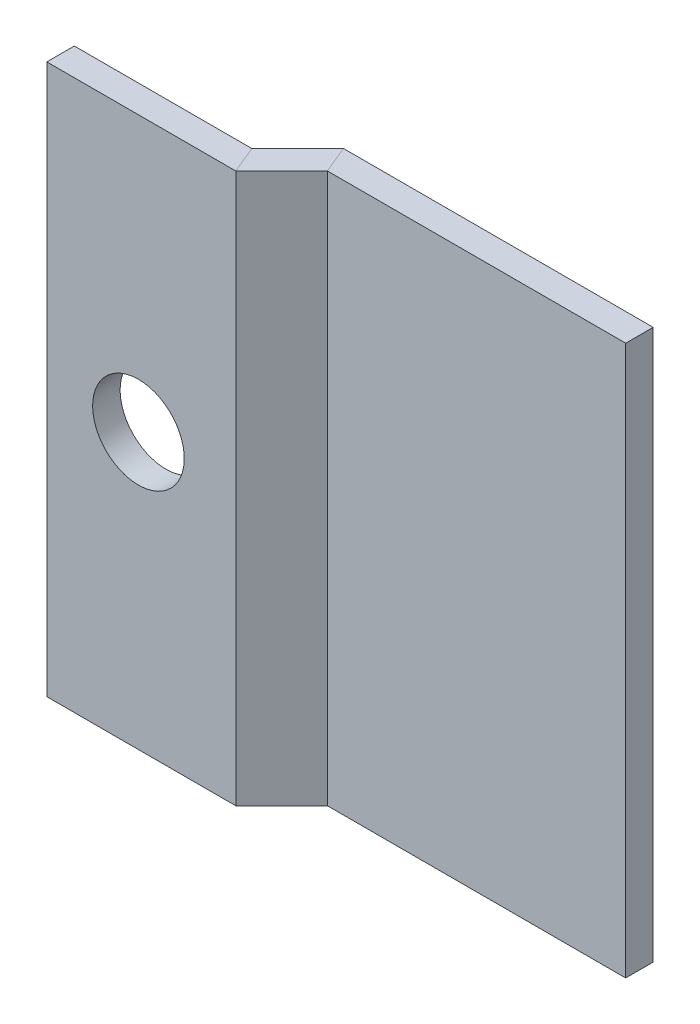
SolidWorks part; units mm, degrees
ref_plane "Front Plane" through (0, 0, 0) normal (0, 0, 1) x (1, 0, 0)
ref_plane "Top Plane" through (0, 0, 0) normal (0, 1, 0) x (1, 0, 0)
ref_plane "Right Plane" through (0, 0, 0) normal (1, 0, 0) x (0, 0, -1)
sketch "Sketch1" plane through (0, 0, 0) normal (0, 1, 0) x (1, 0, 0)
  line L0 (0, 0) -> (4, 0)
  line L1 (4, 0) -> (5, 1)
  line L2 (5, 1) -> (11.6355, 1)
  dimension "D1" = 1
  dimension "D2" = 4
  dimension "D3" = 1
sketch "Sketch2" plane through (0, 0, 0) normal (1, 0, 0) x (0, 0, -1)
  line L1 (-0.3, 6) -> (0.3, 6)
  line L2 (-0.3, 6) -> (-0.3, -6)
  line L3 (-0.3, -6) -> (0.3, -6)
  line L4 (0.3, 6) -> (0.3, -6)
  line L5 (-0.3, 6) -> (0.3, -6) construction
  line L6 (-0.3, -6) -> (0.3, 6) construction
  point P0 (0, 0)
  dimension "D1" = 12
  dimension "D2" = 0.6
sweep "Sweep1" add profiles "Sketch2" path "Sketch1"
sketch "Sketch3" plane through (0, 0, -0.3) normal (0, 0, -1) x (-1, 0, 0)
  line L0 (0, 0) -> (-4, 0) construction
  line L1 (0, -6) -> (0, 6) construction
  circle A0 centre (-2, 0) radius 1
  dimension "D1" = 2
  dimension "D2" = 2
extrude "Cut-Extrude1" cut sketch "Sketch3" against normal blind 0.6
